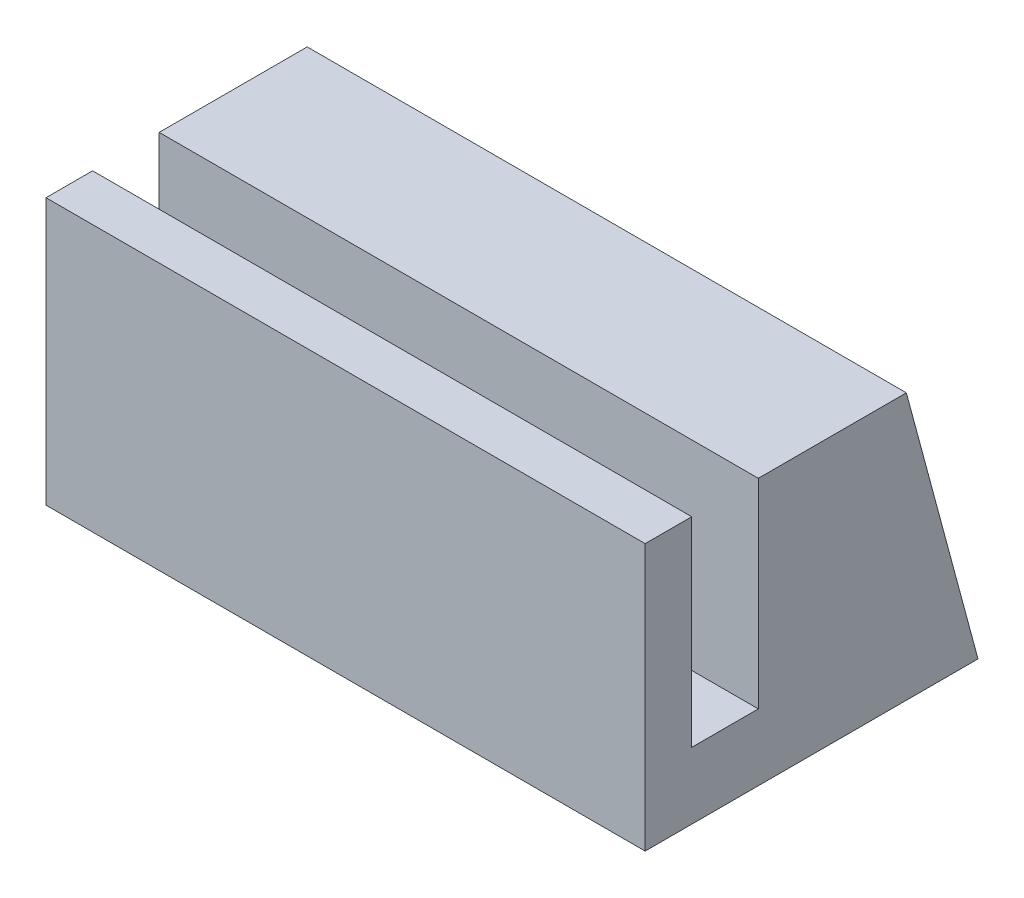
SolidWorks part; units mm, degrees
ref_plane "Front Plane" through (0, 0, 0) normal (0, 0, 1) x (1, 0, 0)
ref_plane "Top Plane" through (0, 0, 0) normal (0, 1, 0) x (1, 0, 0)
ref_plane "Right Plane" through (0, 0, 0) normal (1, 0, 0) x (0, 0, -1)
sketch "Sketch2" plane through (0, 0, 0) normal (0, 0, 1) x (1, 0, 0)
  line L1 (-22.5, -10) -> (22.5, -10)
  line L2 (-22.5, -10) -> (-22.5, 10)
  line L3 (-22.5, 10) -> (22.5, 10)
  line L4 (22.5, -10) -> (22.5, 10)
  line L5 (-22.5, -10) -> (22.5, 10) construction
  line L6 (-22.5, 10) -> (22.5, -10) construction
  point P0 (0, 0)
  dimension "D1" = 45
  dimension "D2" = 20
extrude "Boss-Extrude1" add sketch "Sketch2" along normal blind 25
sketch "Sketch5" plane through (0, 10, 0) normal (0, 1, 0) x (1, 0, 0)
  line L0 (0, 0) -> (0, -15)
  line L1 (0, -15) -> (0, -19)
  line L2 (22.5, -25) -> (22.5, 0) construction
  line L3 (-22.5, -16.5) -> (22.5, -16.5)
  line L4 (-22.5, -16.5) -> (-22.5, -21.5)
  line L5 (-22.5, -21.5) -> (22.5, -21.5)
  line L6 (22.5, -16.5) -> (22.5, -21.5)
  line L7 (-22.5, -16.5) -> (22.5, -21.5) construction
  line L8 (-22.5, -21.5) -> (22.5, -16.5) construction
  dimension "D1" = 15
  dimension "D2" = 4
  dimension "D3" = 5
extrude "Cut-Extrude1" cut sketch "Sketch5" against normal blind 15
sketch "Sketch7" plane through (22.5, 0, 0) normal (1, 0, 0) x (0, 0, -1)
  line L0 (0, -10) -> (0, 10)
  line L1 (0, 10) -> (-5.3816, 10)
  line L2 (-16.5, 10) -> (0, 10) construction
  line L3 (-5.3816, 10) -> (0, -10)
extrude "Cut-Extrude2" cut sketch "Sketch7" against normal up to surface (45 mm away) up to face at (-22.5, 1.25, 15.75)
sketch "Sketch8" plane through (0, -0.6752, 2.5091) normal (0, 0.2598, -0.9657) x (-1, 0, 0)
  line L1 (-19.15, -4.8) -> (19.15, -4.8)
  line L2 (-19.15, -4.8) -> (-19.15, 4.8)
  line L3 (-19.15, 4.8) -> (19.15, 4.8)
  line L4 (19.15, -4.8) -> (19.15, 4.8)
  line L5 (-19.15, -4.8) -> (19.15, 4.8) construction
  line L6 (-19.15, 4.8) -> (19.15, -4.8) construction
  point P0 (0, 0)
  dimension "D1" = 38.3
  dimension "D2" = 9.6
extrude "Cut-Extrude3" cut sketch "Sketch8" against normal blind 10
